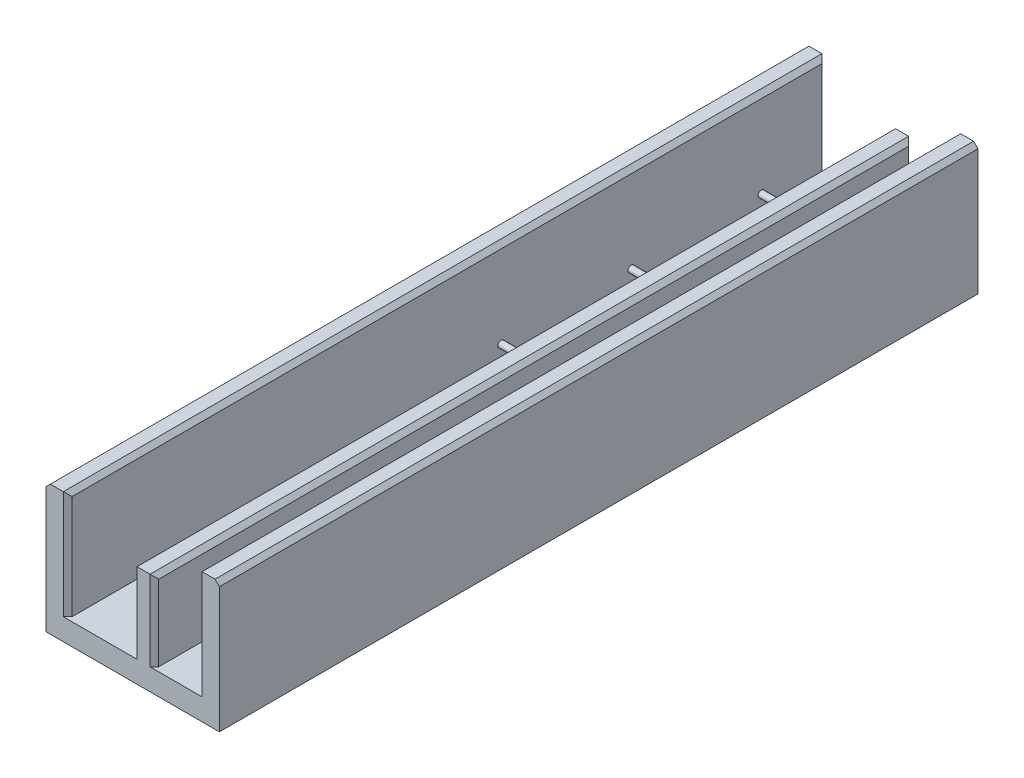
SolidWorks part; units mm, degrees
ref_plane "Alzado" through (0, 0, 0) normal (0, 0, 1) x (1, 0, 0)
ref_plane "Planta" through (0, 0, 0) normal (0, 1, 0) x (1, 0, 0)
ref_plane "Vista lateral" through (0, 0, 0) normal (1, 0, 0) x (0, 0, -1)
sketch "Croquis1" plane through (0, 0, 0) normal (0, 0, 1) x (1, 0, 0)
  line L0 (0, 0) -> (-800, 0)
  line L1 (-800, 0) -> (-800, 600)
  line L2 (-800, 600) -> (-700, 600)
  line L3 (-700, 600) -> (-700, 100)
  line L4 (-700, 100) -> (-400, 100)
  line L5 (-400, 100) -> (-400, 470)
  line L6 (-400, 470) -> (-300, 470)
  line L7 (-300, 470) -> (-300, 100)
  line L8 (-300, 100) -> (-100, 100)
  line L9 (-100, 100) -> (-100, 600)
  line L10 (-100, 600) -> (0, 600)
  line L11 (0, 600) -> (0, 0)
  dimension "D1" = 800
  dimension "D2" = 600
  dimension "D3" = 100
  dimension "D4" = 500
  dimension "D5" = 300
  dimension "D6" = 370
  dimension "D7" = 100
  dimension "D8" = 370
  dimension "D9" = 200
extrude "Saliente-Extruir1" add sketch "Croquis1" along normal blind 3500
chamfer "Chaflán2" distance 20 angle 45 14 edges at (-100, 350, 0) (0, 600, 1750) (-700, 350, 0) (-700, 600, 1750) (-700, 350, 3500) (-100, 350, 3500) (-300, 285, 0) (-300, 285, 3500) (-300, 470, 1750) (-400, 285, 0) (-400, 285, 3500) (-400, 470, 1750) (-800, 600, 1750) (-100, 600, 1750)
sketch "Croquis2" plane through (-800, 0, 0) normal (-1, 0, 0) x (0, 0, 1)
  line L0 (0, 580) -> (0, 0) construction
  circle A0 centre (300, 200) radius 15
  dimension "D3" = 30
  dimension "D1" = 300
extrude "Saliente-Extruir2" add sketch "Croquis2" against normal up to surface (700 mm away) up to face at (-100, 340, 1750)
pattern_linear "MatrizL1" count 3 spacing 600 along (0, 0, 1) of "Saliente-Extruir2"
